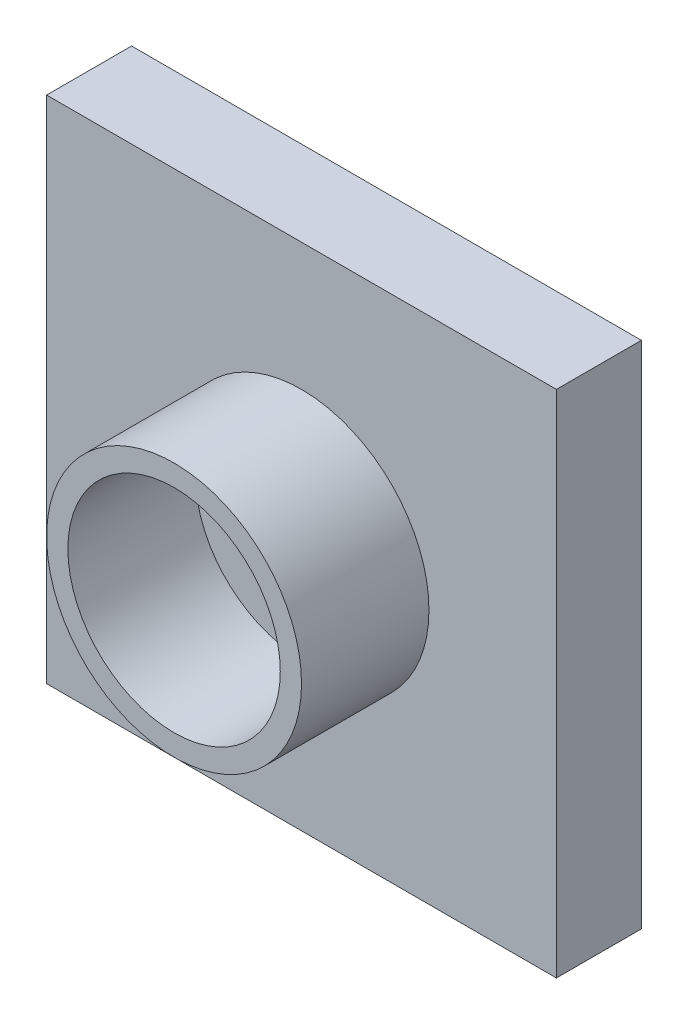
SolidWorks part; units mm, degrees
ref_plane "Front Plane" through (0, 0, 0) normal (0, 0, 1) x (1, 0, 0)
ref_plane "Top Plane" through (0, 0, 0) normal (0, 1, 0) x (1, 0, 0)
ref_plane "Right Plane" through (0, 0, 0) normal (1, 0, 0) x (0, 0, -1)
sketch "Sketch1" plane through (0, 0, 0) normal (0, 0, 1) x (1, 0, 0)
  line L1 (-6, 6) -> (6, 6)
  line L2 (-6, 6) -> (-6, -6)
  line L3 (-6, -6) -> (6, -6)
  line L4 (6, 6) -> (6, -6)
  line L5 (-6, 6) -> (6, -6) construction
  line L6 (-6, -6) -> (6, 6) construction
  point P0 (0, 0)
  dimension "D1" = 12
  dimension "D2" = 12
extrude "Boss-Extrude1" add sketch "Sketch1" along normal blind 2
sketch "Sketch2" plane through (0, 0, 2) normal (0, 0, 1) x (1, 0, 0)
  circle A1 centre (0, 0) radius 2.5
  circle A2 centre (0, 0) radius 3
  dimension "D1" = 6
  dimension "D2" = 5
extrude "Boss-Extrude2" add sketch "Sketch2" along normal blind 3
